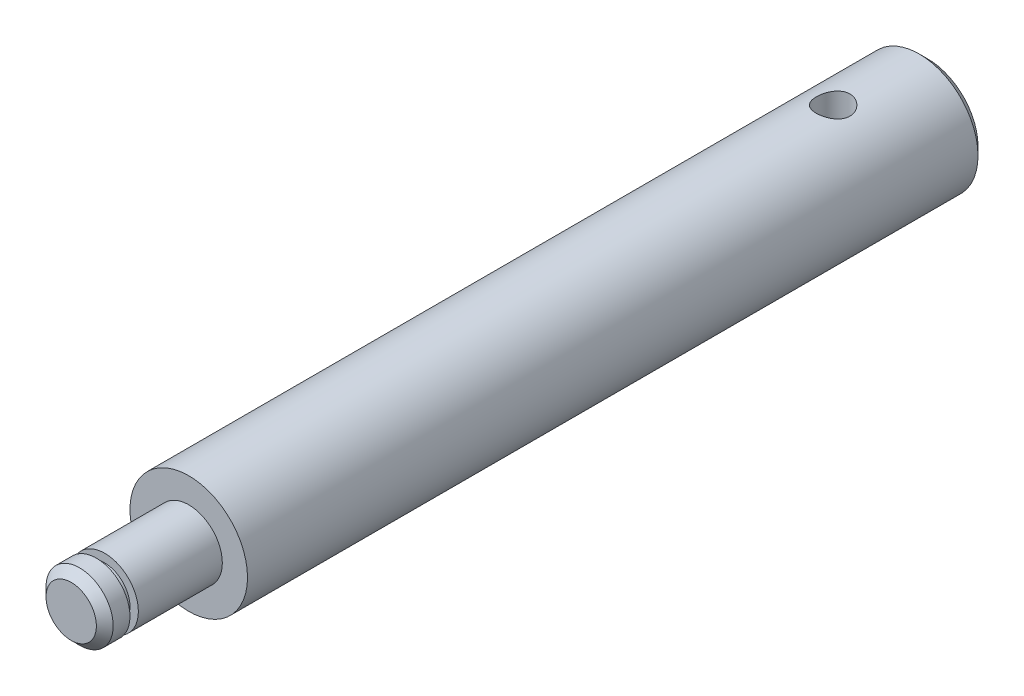
SolidWorks part; units mm, degrees
ref_plane "Plan de face" through (0, 0, 0) normal (0, 0, 1) x (1, 0, 0)
ref_plane "Plan de dessus" through (0, 0, 0) normal (0, 1, 0) x (1, 0, 0)
ref_plane "Plan de droite" through (0, 0, 0) normal (1, 0, 0) x (0, 0, -1)
sketch "Esquisse1" plane through (0, 0, 0) normal (0, 0, 1) x (1, 0, 0)
  circle A0 centre (0, 0) radius 3.5
  dimension "D1" = 7
extrude "Boss.-Extru.1" add sketch "Esquisse1" along normal blind 44
sketch "Esquisse2" plane through (0, 0, 44) normal (0, 0, 1) x (1, 0, 0)
  circle A0 centre (0, 0) radius 2
  dimension "D1" = 4
extrude "Boss.-Extru.2" add sketch "Esquisse2" along normal blind 5
sketch "Esquisse3" plane through (0, 0, 49) normal (0, 0, 1) x (1, 0, 0)
  circle A0 centre (0, 0) radius 1.5
  dimension "D1" = 3
extrude "Boss.-Extru.3" add sketch "Esquisse3" along normal blind 0.5
sketch "Esquisse4" plane through (0, 0, 49.5) normal (0, 0, 1) x (1, 0, 0)
  circle A0 centre (0, 0) radius 2
  dimension "D1" = 4
extrude "Boss.-Extru.4" add sketch "Esquisse4" along normal blind 1.5
chamfer "Chanfrein1" distance 0.5 angle 45 1 edges at (2, 0, 51)
chamfer "Chanfrein2" distance 0.5 angle 45 1 edges at (3.5, 0, 0)
hole_wizard "Diamètre du perçage Ø2.0 (2)3" positions "Esquisse3D1" profile "Esquisse12" hole size "Ø2.0" standard "ISO" end condition through all
sketch3d "Esquisse3D1"
  line L0 (0, 0, 0) -> (0, 0, 5.625) construction
  line L2 (0, 3.5, 5.625) -> (0, 0, 5.625) construction
  point P0 (0, 3.5, 5.625)
  dimension "D1" = 5.625
sketch "Esquisse12" plane through (0, 3.5, 5.625) normal (1, 0, 0) x (0, 0, 1)
  line L0 (0, 0) -> (0, 7)
  line L1 (0, 7) -> (1, 7)
  line L2 (1, 7) -> (1, 0)
  line L5 (1, 0) -> (0, 0)
  line L11 (0, -6.35) -> (0, 107.95) construction
  dimension "Diamètre du perçage jusqu'au prochain" = 2
  dimension "Profondeur du perçage jusqu'au prochain" = 7
cosmetic thread "Représentation de filetage1" parameters "D2"=3
